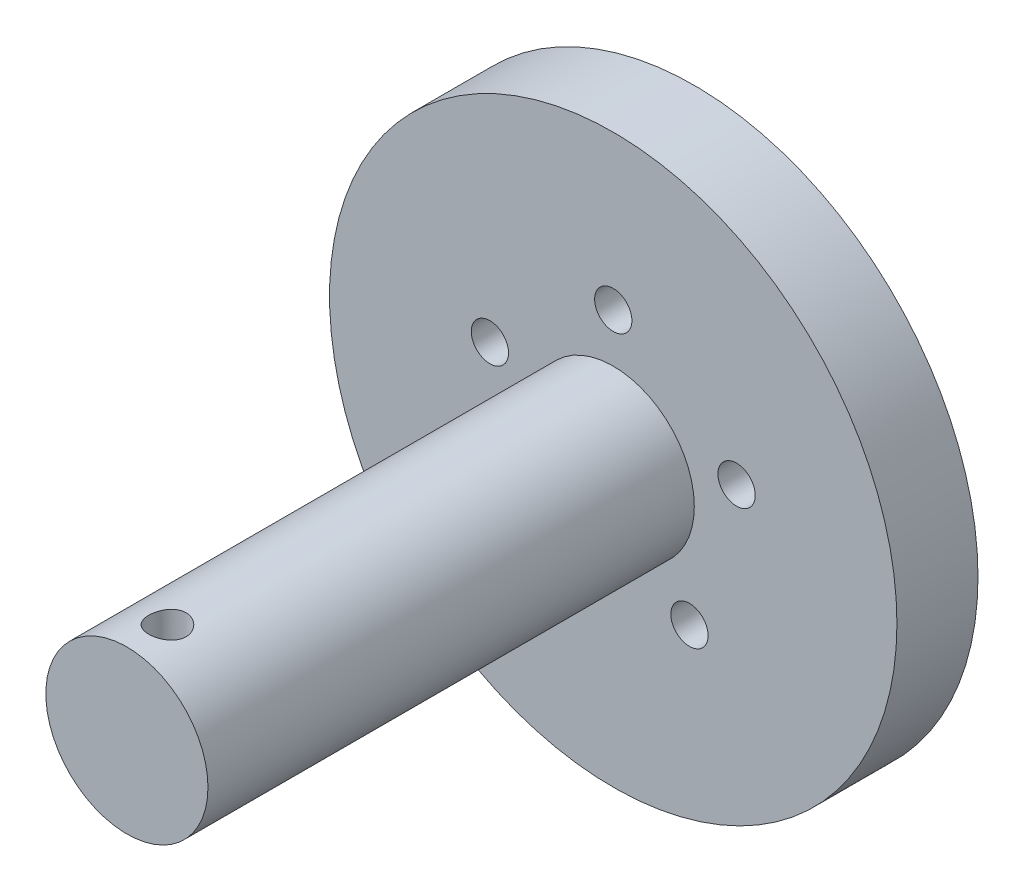
SolidWorks part; units mm, degrees
ref_plane "Front Plane" through (0, 0, 0) normal (0, 0, 1) x (1, 0, 0)
ref_plane "Top Plane" through (0, 0, 0) normal (0, 1, 0) x (1, 0, 0)
ref_plane "Right Plane" through (0, 0, 0) normal (1, 0, 0) x (0, 0, -1)
sketch "Sketch1" plane through (0, 0, 0) normal (0, 0, 1) x (1, 0, 0)
  line L0 (0, 0) -> (0, 20.32) construction
  line L1 (0, 0) -> (19.3255, 6.2792) construction
  line L2 (0, 0) -> (11.9438, -16.4392) construction
  line L3 (0, 0) -> (-11.9438, -16.4392) construction
  line L4 (0, 0) -> (-19.3255, 6.2792) construction
  circle A0 centre (0, 0) radius 44.45
  circle A1 centre (0, 20.32) radius 2.921
  circle A2 centre (19.3255, 6.2792) radius 2.921
  circle A3 centre (11.9438, -16.4392) radius 2.921
  circle A4 centre (-11.9438, -16.4392) radius 2.921
  circle A5 centre (-19.3255, 6.2792) radius 2.921
  point P15 (0, 0)
  dimension "D1" = 88.9
  dimension "D3" = 5.842
  dimension "D2" = 20.32
  dimension "D4" = 5
extrude "Boss-Extrude1" add sketch "Sketch1" along normal blind 12.7
sketch "Sketch2" plane through (0, 0, 12.7) normal (0, 0, 1) x (1, 0, 0)
  circle A0 centre (0, 0) radius 12.7
  dimension "D1" = 25.4
extrude "Boss-Extrude2" add sketch "Sketch2" along normal blind 76.2
sketch "Sketch3" plane through (0, 0, 88.9) normal (0, 0, 1) x (1, 0, 0)
  line L0 (0, 0) -> (0, -12.7) construction
  circle A0 centre (0, 0) radius 12.7 construction
ref_plane "Plane1" through (0, -12.7, 0) normal (0, -1, 0) x (-1, 0, 0)
sketch "Sketch4" plane through (0, -12.7, 0) normal (0, -1, 0) x (-1, 0, 0)
  line L0 (0, -88.9) -> (0, -82.55) construction
  line L1 (-12.7, -88.9) -> (12.7, -88.9) construction
  circle A0 centre (0, -82.55) radius 2.921
  dimension "D2" = 5.842
  dimension "D1" = 6.35
extrude "Cut-Extrude1" cut sketch "Sketch4" against normal up to next
